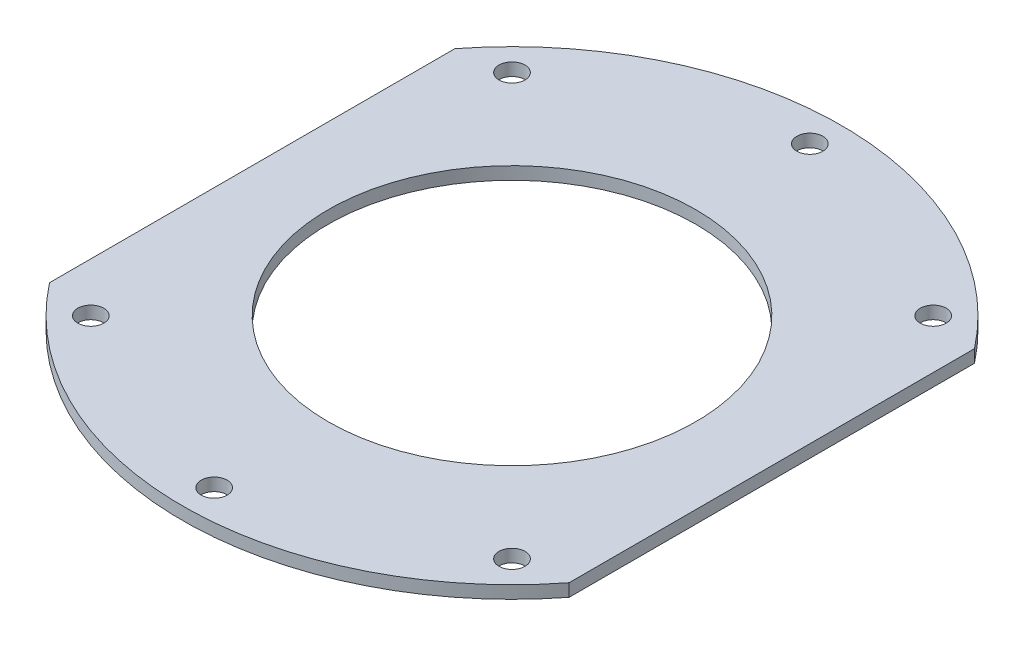
SolidWorks part; units mm, degrees
ref_plane "前视基准面" through (0, 0, 0) normal (0, 0, 1) x (1, 0, 0)
ref_plane "上视基准面" through (0, 0, 0) normal (0, 1, 0) x (1, 0, 0)
ref_plane "右视基准面" through (0, 0, 0) normal (1, 0, 0) x (0, 0, -1)
sketch "草图1" plane through (0, 0, 0) normal (0, 1, 0) x (1, 0, 0)
  circle A0 centre (0, 0) radius 29
  circle A1 centre (0, 0) radius 52
  circle A2 centre (47, 0) radius 2.05
  circle A3 centre (33.234, -33.234) radius 2.05
  circle A4 centre (0, -47) radius 2.05
  circle A5 centre (-33.234, -33.234) radius 2.05
  circle A6 centre (-47, 0) radius 2.05
  circle A7 centre (-33.234, 33.234) radius 2.05
  circle A8 centre (0, 47) radius 2.05
  circle A9 centre (33.234, 33.234) radius 2.05
  circle A10 centre (0, 0) radius 43 construction
  point P6 (52, 0)
  point P9 (43, 0)
  dimension "D1" = 58
  dimension "D2" = 86
  dimension "D3" = 4
  dimension "D4" = 4.1
  dimension "D7" = 5
  dimension "D5" = 8
extrude "凸台-拉伸1" add sketch "草图1" along normal blind 2
sketch "草图2" plane through (0, 2, 0) normal (0, 1, 0) x (1, 0, 0)
  line L1 (-41, -55.0176) -> (41, -55.0176)
  line L2 (-41, -55.0176) -> (-41, 55.0176)
  line L3 (-41, 55.0176) -> (41, 55.0176)
  line L4 (41, -55.0176) -> (41, 55.0176)
  line L5 (-41, -55.0176) -> (41, 55.0176) construction
  line L6 (-41, 55.0176) -> (41, -55.0176) construction
  point P0 (0, 0)
  dimension "D1" = 82
extrude "切除-拉伸-薄壁1" cut sketch "草图2" against normal blind 10 thin
